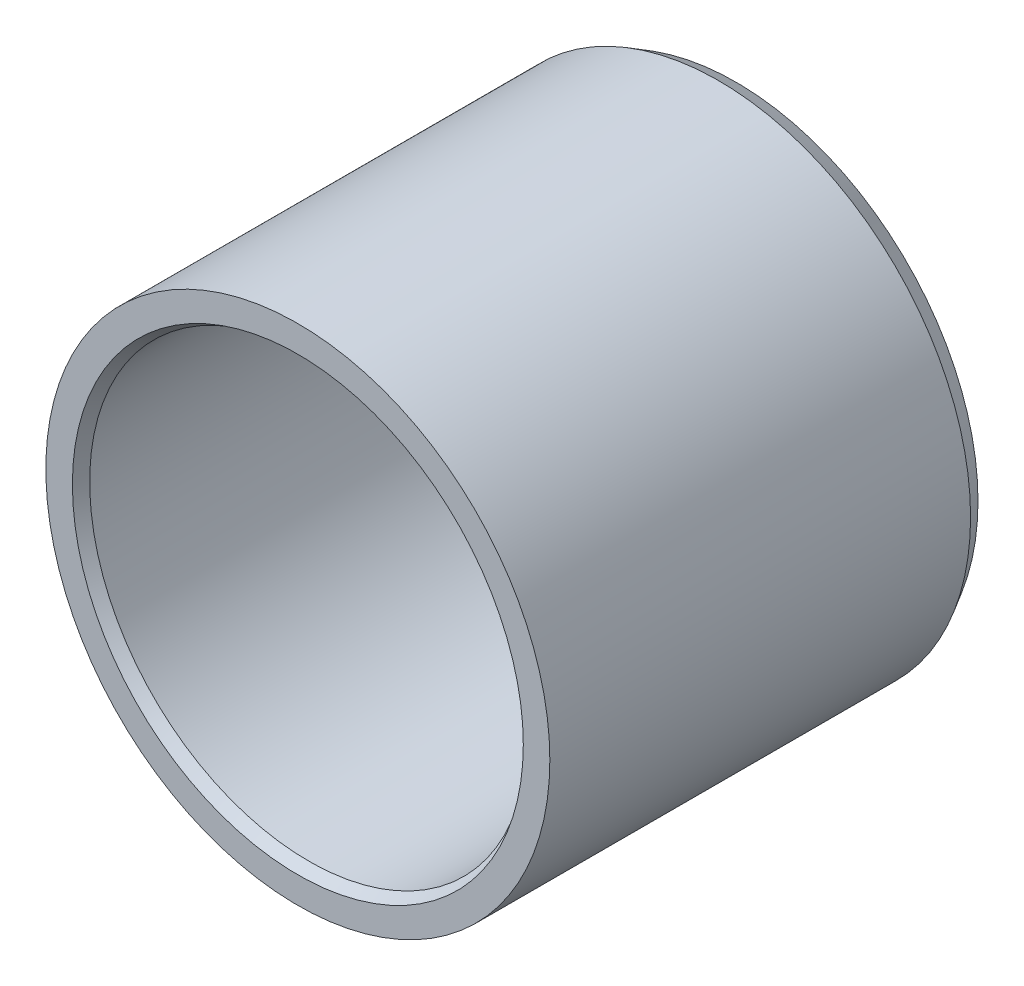
SolidWorks part; units mm, degrees
ref_plane "Přední rovina" through (0, 0, 0) normal (0, 0, 1) x (1, 0, 0)
ref_plane "Vrchní rovina" through (0, 0, 0) normal (0, 1, 0) x (1, 0, 0)
ref_plane "Pravá rovina" through (0, 0, 0) normal (1, 0, 0) x (0, 0, -1)
sketch "Skica1" plane through (0, 0, 0) normal (0, 0, 1) x (1, 0, 0)
  circle A0 centre (0, 0) radius 10
  circle A1 centre (0, 0) radius 11.5
  dimension "d1" = 20
  dimension "d2" = 23
extrude "Vysunout1" add sketch "Skica1" along normal blind 20
chamfer "Zkosit1" distance 0.5 angle 30 1 edges at (10, 0, 20)
chamfer "Zkosit2" distance 0.8 angle 30 1 edges at (11.5, 0, 0)
